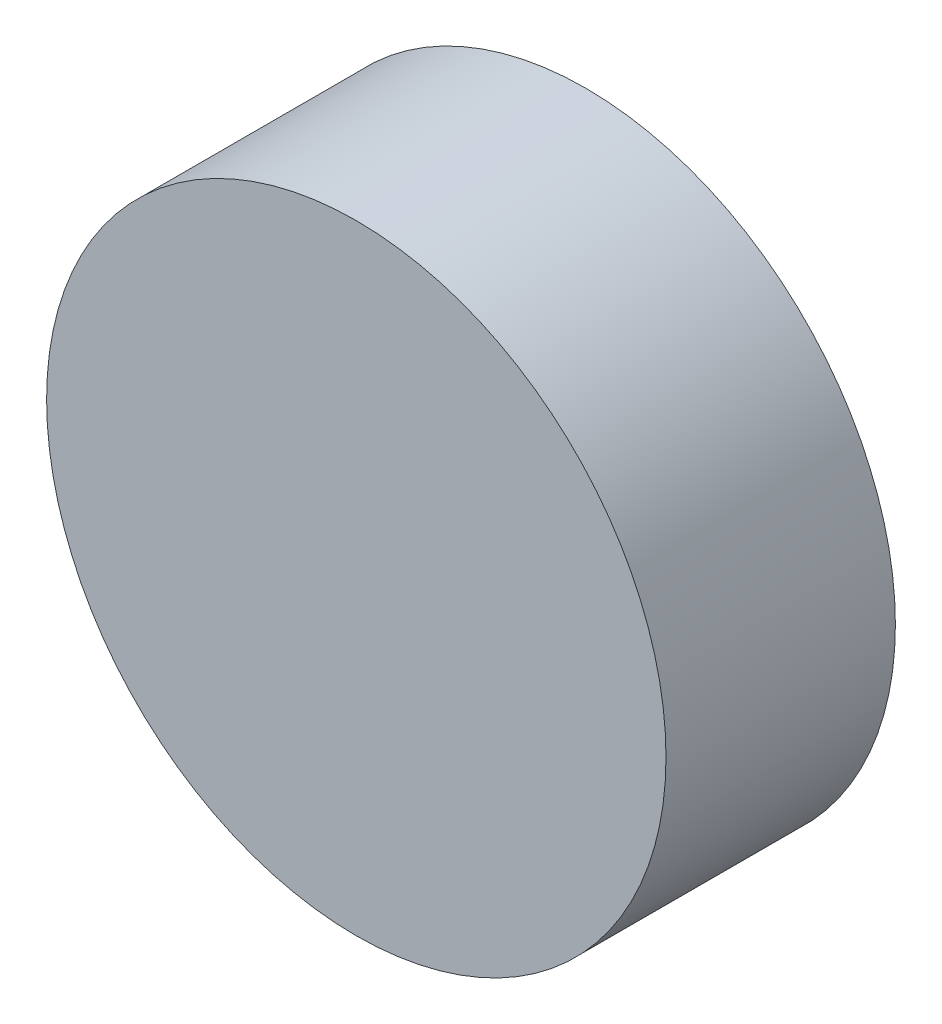
SolidWorks part; units mm, degrees
ref_plane "Plan1" through (0, 0, 0) normal (0, 0, 1) x (1, 0, 0)
ref_plane "Plan2" through (0, 0, 0) normal (0, 1, 0) x (1, 0, 0)
ref_plane "Plan3" through (0, 0, 0) normal (1, 0, 0) x (0, 0, -1)
sketch "Esquisse1" plane through (0, 0, 0) normal (0, 0, 1) x (1, 0, 0)
  circle A0 centre (0, 0) radius 13.5
  dimension "D1" = 27
extrude "Base-Extrusion" add sketch "Esquisse1" along normal blind 10
